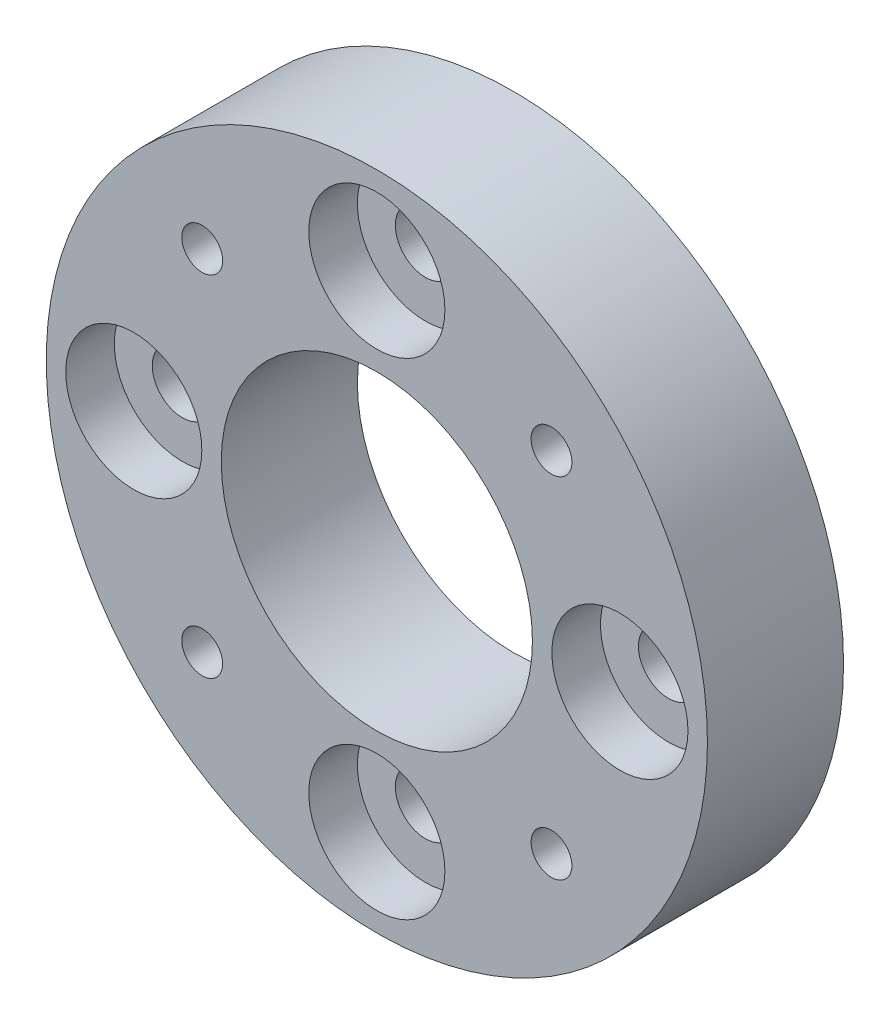
SolidWorks part; units mm, degrees
ref_plane "Front Plane" through (0, 0, 0) normal (0, 0, 1) x (1, 0, 0)
ref_plane "Top Plane" through (0, 0, 0) normal (0, 1, 0) x (1, 0, 0)
ref_plane "Right Plane" through (0, 0, 0) normal (1, 0, 0) x (0, 0, -1)
sketch "Sketch1" plane through (0, 0, 0) normal (0, 0, 1) x (1, 0, 0)
  circle A0 centre (0, 0) radius 17
  circle A1 centre (0, 0) radius 12.7 construction
  circle A2 centre (0, 0) radius 12.5 construction
  circle A3 centre (0, 12.5) radius 1.55
  circle A4 centre (12.5, 0) radius 1.55
  circle A5 centre (0, -12.5) radius 1.55
  circle A6 centre (-12.5, 0) radius 1.55
  circle A7 centre (-8.9803, 8.9803) radius 1.05
  circle A8 centre (8.9803, 8.9803) radius 1.05
  circle A9 centre (8.9803, -8.9803) radius 1.05
  circle A10 centre (-8.9803, -8.9803) radius 1.05
  circle A11 centre (0, 0) radius 8
  point P16 (0, 0)
  point P25 (0, 0)
  dimension "D1" = 4
  dimension "D2" = 4
extrude "Boss-Extrude1" add sketch "Sketch1" along normal blind 7
sketch "Sketch2" plane through (0, 0, 7) normal (0, 0, 1) x (1, 0, 0)
  circle A0 centre (0, 12.5) radius 3.5
  circle A1 centre (12.5, 0) radius 3.5
  circle A2 centre (0, -12.5) radius 3.5
  circle A3 centre (-12.5, 0) radius 3.5
  point P12 (0, 0)
  dimension "D1" = 4
extrude "Cut-Extrude2" cut sketch "Sketch2" against normal blind 2.5
